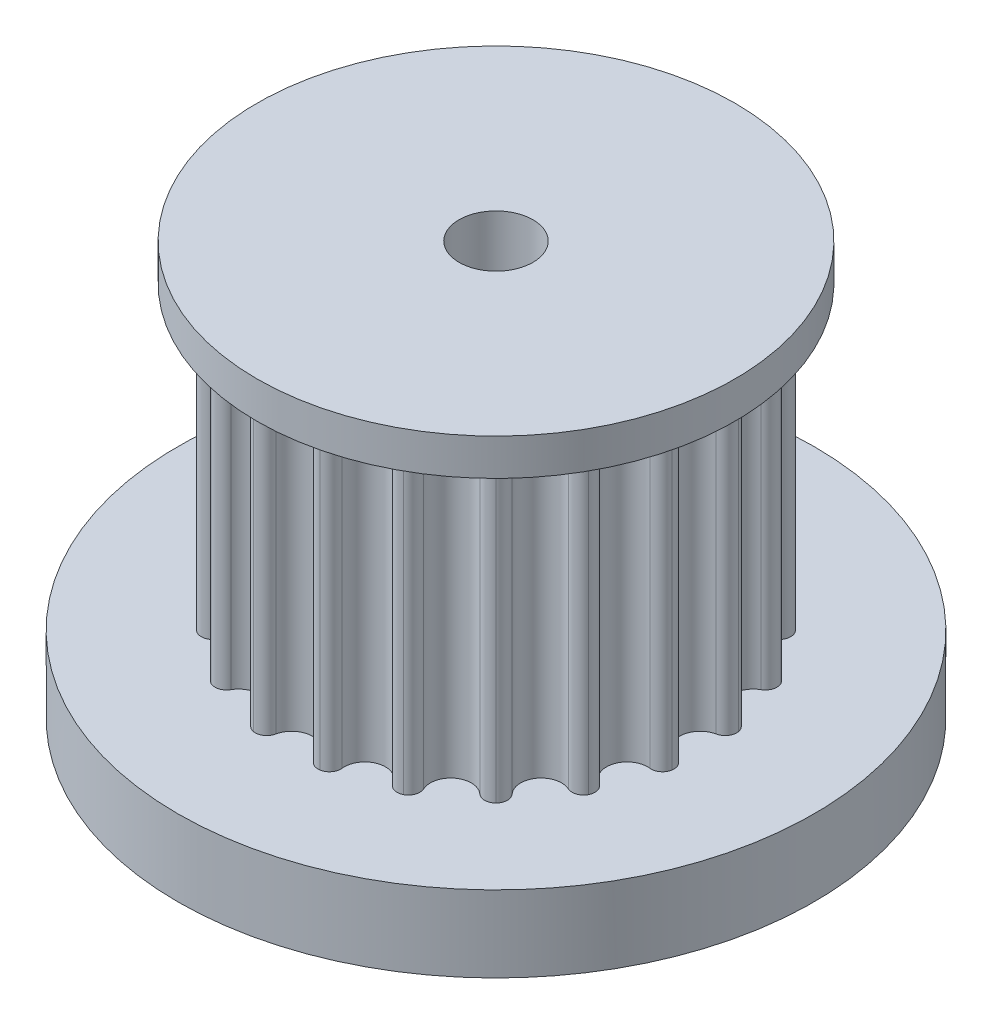
SolidWorks part; units mm, degrees
ref_plane "Front Plane" through (0, 0, 0) normal (0, 0, 1) x (1, 0, 0)
ref_plane "Top Plane" through (0, 0, 0) normal (0, 1, 0) x (1, 0, 0)
ref_plane "Right Plane" through (0, 0, 0) normal (1, 0, 0) x (0, 0, -1)
sketch "Sketch1" plane through (0, 0, 0) normal (0, 1, 0) x (1, 0, 0)
  line L0 (0, 0) -> (0, 9.1676) construction
  line L1 (0, 0) -> (2.731, 8.405) construction
  circle A0 centre (0, 0) radius 9.1676 construction
  circle A1 centre (0, 0) radius 7.9476 construction
  circle A2 centre (0, 8.8376) radius 0.89 construction
  circle A5 centre (2.731, 8.405) radius 0.89 construction
  arc A6 (0, 7.9476) -> (0.8721, 8.6598) centre (0, 8.8376) ccw
  arc A7 (0.8721, 8.6598) -> (1.4405, 9.0537) centre (1.362, 8.5599) cw
  arc A8 (1.4277, 9.0557) -> (1.8466, 8.5054) centre (1.3498, 8.5618) cw
  arc A9 (2.4559, 7.5586) -> (1.8466, 8.5054) centre (2.731, 8.405) cw
  arc A10 (1.4405, 9.0537) -> (1.4277, 9.0557) centre (0, 0) cw
  arc A11 (0, 7.9476) -> (2.4559, 7.5586) centre (0, 0) ccw
  dimension "D1" = 18.3352
  dimension "D3" = 1.78
  dimension "D4" = 0.5
  dimension "D2" = 1.22
  dimension "D5" = 18
extrude "Boss-Extrude1" add sketch "Sketch1" along normal mid plane 13 contours A6 A11 A9 A8 A7
ref_axis "Axis1" through (0, 3.3, 0) along (0, -1, 0)
pattern_circular "CirPattern1" count 20 over 360 about axis through (0, 0, 0) along (0, 1, 0) of "Boss-Extrude1"
sketch "Sketch2" plane through (0, 0, 0) normal (1, 0, 0) x (0, 0, -1)
  line L10 (0, 6.5) -> (10.3423, 6.5) construction
  line L11 (0, 6.5) -> (0, 8.0875) construction
  line L12 (0, 8.0875) -> (10.3423, 8.0875) construction
  line L15 (10.3423, 6.5) -> (10.3423, 8.0875) construction
  line L20 (0, 3.3) -> (0, -3.3) construction
  line L22 (10.3423, 8.0875) -> (0, 8.0875)
  line L23 (10.3423, 8.0875) -> (10.3423, 6.5)
  line L24 (10.3423, 6.5) -> (0, 6.5)
  line L25 (0, 8.0875) -> (0, 6.5)
  dimension "D1" = 1.5875
  dimension "D2" = 10.3423
  dimension "D3" = 6.5
revolve "Revolve3" add sketch "Sketch2" angle 360 about axis through (0, 3.3, 0) along (0, -1, 0)
sketch "Sketch3" plane through (0, 0, 0) normal (0, -1, 0) x (-1, 0, 0)
  circle A0 centre (0, 0) radius 1.6
  dimension "D1" = 3.2
extrude "Cut-Extrude1" cut sketch "Sketch3" against normal through all both and the other way through all
sketch "Sketch4" plane through (0, -9.8025, 0) normal (0, 1, 0) x (1, 0, 0)
  circle A0 centre (0, 0) radius 13.77
  circle A1 centre (0, 0) radius 12.5 construction
  dimension "D1" = 1.27
extrude "Boss-Extrude2" add sketch "Sketch4" along normal up to surface (3.3025 mm away) up to face at (0, -6.5, -1.6)
sketch "Sketch5" plane through (0, -9.8025, 0) normal (0, 1, 0) x (1, 0, 0)
  line L6 (-2.9173, 4.6617) -> (-5.4958, -0.1956)
  line L7 (-5.4958, -0.1956) -> (-2.5785, -4.8573)
  line L8 (-2.5785, -4.8573) -> (2.9173, -4.6617)
  line L9 (2.9173, -4.6617) -> (5.4958, 0.1956)
  line L10 (5.4958, 0.1956) -> (2.5785, 4.8573)
  line L11 (2.5785, 4.8573) -> (-2.9173, 4.6617)
  line L12 (-2.9173, 4.6617) -> (-5.4958, -0.1956)
  line L13 (-5.4958, -0.1956) -> (-2.5785, -4.8573)
  line L14 (-2.5785, -4.8573) -> (2.9173, -4.6617)
  line L15 (2.9173, -4.6617) -> (5.4958, 0.1956)
  line L16 (5.4958, 0.1956) -> (2.5785, 4.8573)
  line L17 (2.5785, 4.8573) -> (-2.9173, 4.6617)
  dimension "D1" = 0
extrude "Cut-Extrude2" cut sketch "Sketch5" along normal offset from surface (13.208 mm away) 0.508
equation "\"TEETH_NUM\"= 20"
equation "\"TOOTH_PITCH\"= 3mm"
equation "\"PITCH_LINE_OFFSET\"= .015in"
equation "\"DIAMETER_PER_GROOVE\"= \"OUTSIDE_DIAMETER\" / \"TEETH_NUM\" * 1in"
equation "\"PITCH_DIAMETER\"= ( ( \"TEETH_NUM\" * 3 - 1.31 ) / 3.1415 + .415 ) * 1mm"
equation "\"OUTSIDE_DIAMETER\"= \"PITCH_DIAMETER\" - \"PITCH_LINE_OFFSET\" * 2"
equation "\"D1@Sketch1\"=\"OUTSIDE_DIAMETER\""
equation "\"TOOTH_HEIGHT\"= 1.22mm"
equation "\"D2@Sketch1\"=\"TOOTH_HEIGHT\""
equation "\"TOOTH_DIAMETER\"= 1.78mm"
equation "\"INTERNAL_RADIUS\"= .5mm"
equation "\"D3@Sketch1\"=\"TOOTH_DIAMETER\""
equation "\"D5@Sketch1\"=360 / \"TEETH_NUM\""
equation "\"D4@Sketch1\"=\"INTERNAL_RADIUS\""
equation "\"D1@CirPattern1\"=\"TEETH_NUM\""
equation "\"BELT_GAP\"= 13mm"
equation "\"D2@Sketch2\"=\"PITCH_DIAMETER\"/2+1/32"
equation "\"D3@Sketch2\"=\"BELT_GAP\"/2"
equation "\"D1@Boss-Extrude1\"=\"BELT_GAP\""
